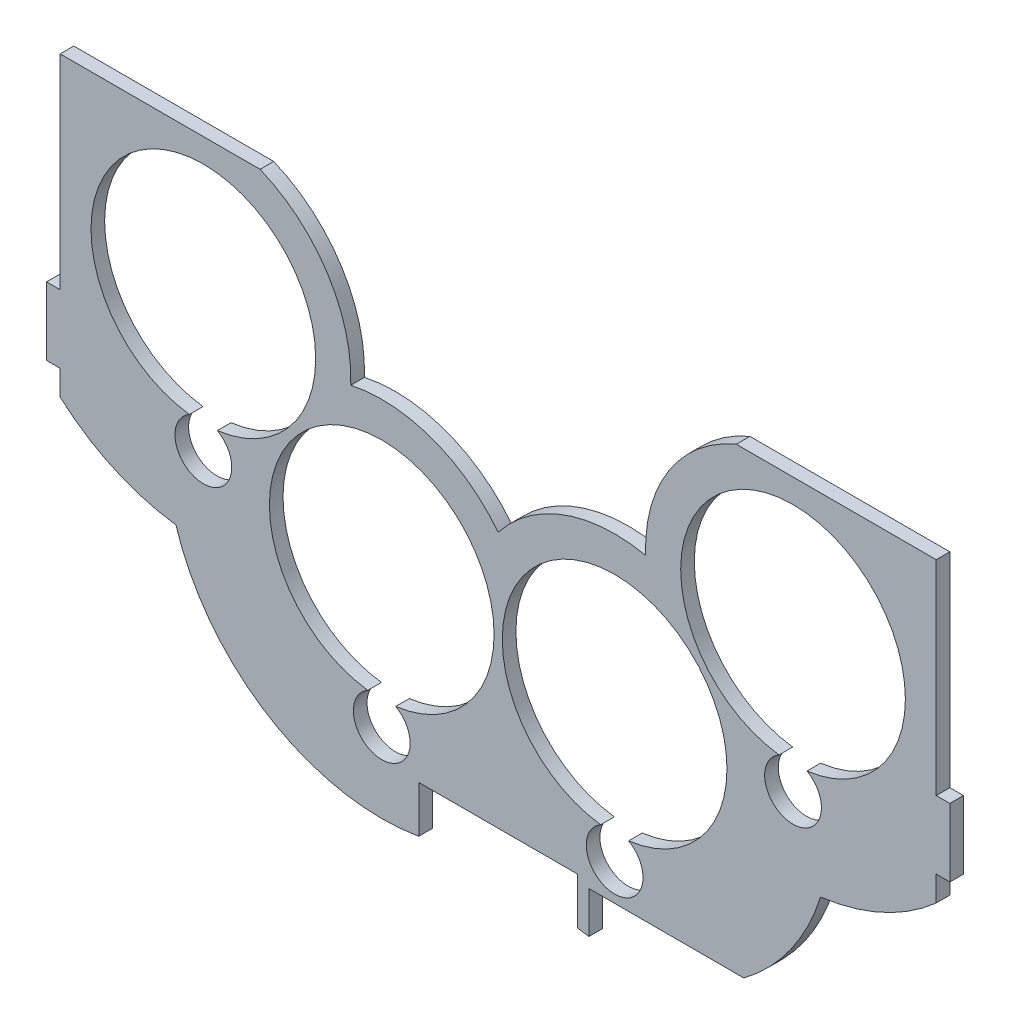
SolidWorks part; units mm, degrees
ref_plane "Спереди" through (0, 0, 0) normal (0, 0, 1) x (1, 0, 0)
ref_plane "Сверху" through (0, 0, 0) normal (0, 1, 0) x (1, 0, 0)
ref_plane "Справа" through (0, 0, 0) normal (1, 0, 0) x (0, 0, -1)
sketch "Эскиз1" plane through (0, 0, 0) normal (0, 0, 1) x (1, 0, 0)
  line L0 (101.0962, 190) -> (231, 265) construction
  line L15 (0, 265) -> (450, 265) construction
  line L17 (179.697, 124.0461) -> (231, 265) construction
  line L18 (231, 265) -> (282.303, 124.0461) construction
  line L19 (231, 265) -> (360.9038, 190) construction
  line L46 (424, 250) -> (424, 160)
  line L48 (424, 160) -> (430, 160)
  line L65 (430, 160) -> (430, 130)
  line L68 (430, 130) -> (424, 130)
  line L103 (196, 51) -> (266, 51)
  line L104 (196, 51) -> (196, 30.4554)
  line L106 (266, 51) -> (266, 30.4554)
  line L108 (38, 250) -> (38, 160)
  line L109 (38, 160) -> (32, 160)
  line L110 (32, 160) -> (32, 130)
  line L111 (32, 130) -> (38, 130)
  line L112 (38, 130) -> (38, 118.9798)
  line L113 (424, 130) -> (424, 118.9798)
  line L114 (38, 250) -> (126.0962, 250)
  line L115 (335.9038, 250) -> (424, 250)
  line L116 (271, 48) -> (339.2415, 48)
  line L118 (271, 29.7209) -> (271, 48)
  arc A7 (107.2446, 140.8833) -> (94.9478, 140.8833) centre (101.0962, 190) ccw
  arc A8 (185.8454, 74.9294) -> (173.5486, 74.9294) centre (179.697, 124.0461) ccw
  arc A9 (288.4514, 74.9294) -> (276.1546, 74.9294) centre (282.303, 124.0461) ccw
  arc A10 (367.0522, 140.8833) -> (354.7554, 140.8833) centre (360.9038, 190) ccw
  arc A23 (166.0518, 187.5977) -> (126.0962, 250) centre (101.0962, 190) ccw
  arc A24 (89.0017, 95.773) -> (196, 30.4554) centre (179.697, 124.0461) ccw
  arc A26 (266, 30.4554) -> (271, 29.7209) centre (282.303, 124.0461) ccw
  arc A27 (372.9983, 95.773) -> (424, 118.9798) centre (360.9038, 190) ccw
  arc A29 (38, 118.9798) -> (89.0017, 95.773) centre (101.0962, 190) ccw
  arc A30 (94.9478, 140.8833) -> (107.2446, 140.8833) centre (101.0962, 130) ccw
  arc A31 (173.5486, 74.9294) -> (185.8454, 74.9294) centre (179.697, 64.0461) ccw
  arc A32 (276.1546, 74.9294) -> (288.4514, 74.9294) centre (282.303, 64.0461) ccw
  arc A33 (354.7554, 140.8833) -> (367.0522, 140.8833) centre (360.9038, 130) ccw
  arc A35 (335.9038, 250) -> (295.9482, 187.5977) centre (360.9038, 190) ccw
  arc A36 (231, 163.9585) -> (166.0518, 187.5977) centre (179.697, 124.0461) ccw
  arc A37 (295.9482, 187.5977) -> (231, 163.9585) centre (282.303, 124.0461) ccw
  arc A38 (339.2415, 48) -> (372.9983, 95.773) centre (282.303, 124.0461) ccw
  point P4 (231, 51)
  point P17 (231, 265)
  point P52 (225, 250)
  dimension "D4" = 30
  dimension "D5" = 99
  dimension "D6" = 150
  dimension "D7" = 4
  dimension "D8" = 40
  dimension "D9" = 40
  dimension "D12" = 15
  dimension "D54" = 95
  dimension "D55" = 95
  dimension "D56" = 95
  dimension "D66" = 25
  dimension "D67" = 25
  dimension "D68" = 25
  dimension "D69" = 25
  dimension "D18" = 65
  dimension "D42" = 65
  dimension "D44" = 65
  dimension "D45" = 65
  dimension "D22" = 95
  dimension "D3" = 265
  dimension "D10" = 40
  dimension "D11" = 193
  dimension "D13" = 30
  dimension "D14" = 6
  dimension "D15" = 6
  dimension "D16" = 6
  dimension "D17" = 6
  dimension "D19" = 38
  dimension "D20" = 90
  dimension "D21" = 386
  dimension "D23" = 70
  dimension "D24" = 20.5446
  dimension "D25" = 5
  dimension "D26" = 3
  dimension "D57" = 60
  dimension "D58" = 60
  dimension "D59" = 60
  dimension "D60" = 60
extrude "Бобышка-Вытянуть1" add sketch "Эскиз1" along normal blind 6
